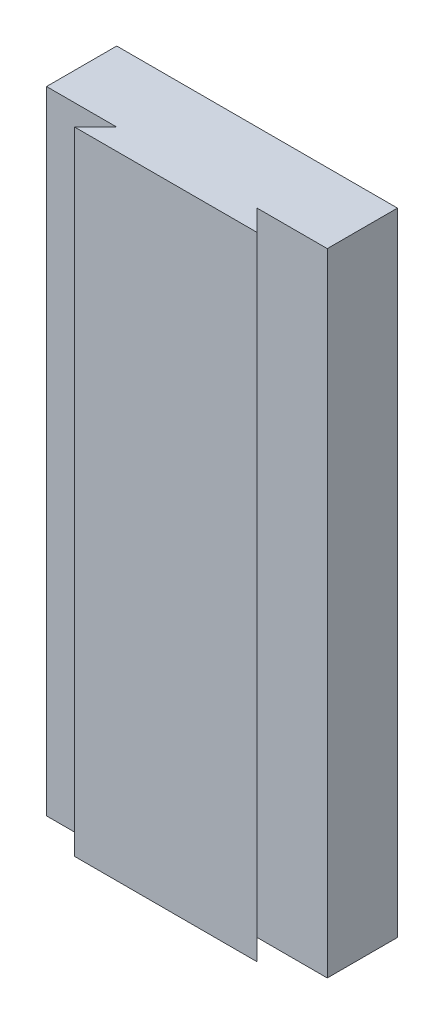
SolidWorks part; units mm, degrees
ref_plane "前视基准面" through (0, 0, 0) normal (0, 0, 1) x (1, 0, 0)
ref_plane "上视基准面" through (0, 0, 0) normal (0, 1, 0) x (1, 0, 0)
ref_plane "右视基准面" through (0, 0, 0) normal (1, 0, 0) x (0, 0, -1)
other "Configuration Table"
sketch "草图1" plane through (0, 0, 0) normal (0, 0, 1) x (1, 0, 0)
  line L1 (0, 0) -> (40, 0)
  line L2 (0, 0) -> (0, -90)
  line L3 (0, -90) -> (40, -90)
  line L4 (40, 0) -> (40, -90)
  dimension "D1" = 40
  dimension "D2" = 90
extrude "凸台-拉伸1" add sketch "草图1" along normal blind 10
sketch "草图2" plane through (0, -90, 0) normal (0, -1, 0) x (1, 0, 0)
  line L0 (10, 10) -> (7, 13)
  line L1 (0, 10) -> (40, 10) construction
  line L2 (7, 13) -> (33, 13)
  line L3 (33, 13) -> (30, 10)
  line L4 (0, 10) -> (0, 0) construction
  line L5 (40, 10) -> (40, 0) construction
  line L6 (10, 10) -> (30, 10)
  dimension "D1" = 10
  dimension "D2" = 10
  dimension "D3" = 26
  dimension "D4" = 3
  dimension "D5" = 7
extrude "凸台-拉伸2" add sketch "草图2" against normal up to surface (90 mm away) up to face at (20, 0, 5)
